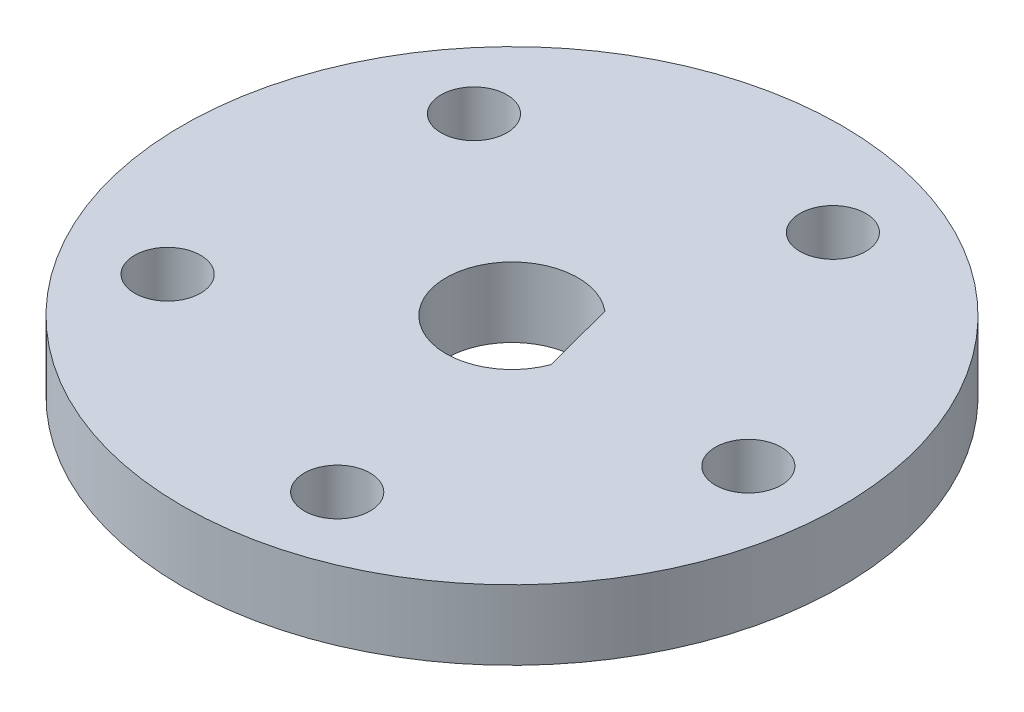
SolidWorks part; units mm, degrees
ref_plane "Front" through (0, 0, 0) normal (0, 0, 1) x (1, 0, 0)
ref_plane "Top" through (0, 0, 0) normal (0, 1, 0) x (1, 0, 0)
ref_plane "Right" through (0, 0, 0) normal (1, 0, 0) x (0, 0, -1)
sketch "Sketch1" plane through (0, 0, 0) normal (0, 1, 0) x (1, 0, 0)
  circle A0 centre (0, 0) radius 15
  circle A1 centre (-8.8254, 7.0937) radius 1.5
  circle A2 centre (4.0193, 10.5855) radius 1.5
  circle A3 centre (11.3094, -0.5515) radius 1.5
  circle A4 centre (2.9703, -10.9263) radius 1.5
  circle A5 centre (-9.4737, -6.2014) radius 1.5
  dimension "D1" = 30
extrude "Boss-Extrude1" add sketch "Sketch1" along normal blind 3.175
sketch "Sketch2" plane through (0, 3.175, 0) normal (0, 1, 0) x (1, 0, 0)
  line L0 (1.9347, 2.2928) -> (2.8187, -1.0272)
  circle A0 centre (0, 0) radius 3
  dimension "D1" = 3.32
extrude "Cut-Extrude1" cut sketch "Sketch2" against normal blind 3.175 contours L0 A0
